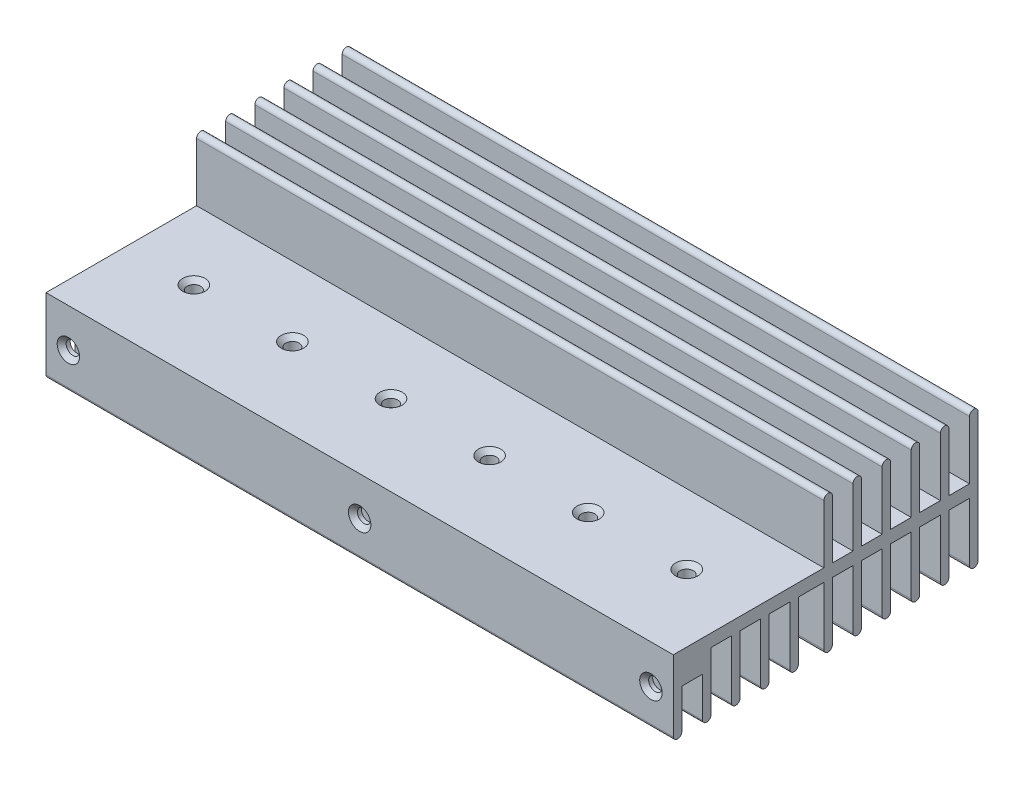
SolidWorks part; units mm, degrees
ref_plane "Front Plane" through (0, 0, 0) normal (0, 0, 1) x (1, 0, 0)
ref_plane "Top Plane" through (0, 0, 0) normal (0, 1, 0) x (1, 0, 0)
ref_plane "Right Plane" through (0, 0, 0) normal (1, 0, 0) x (0, 0, -1)
sketch "Sketch1" plane through (0, 0, 0) normal (1, 0, 0) x (0, 0, -1)
  line L0 (34, 14.4) -> (34, -14.4)
  line L1 (-34, 15.35) -> (34, 15.35) construction
  line L2 (-34, 15.35) -> (-34, -15.35) construction
  line L3 (-34, -15.35) -> (34, -15.35) construction
  line L4 (34, 15.35) -> (34, -15.35) construction
  line L5 (-34, 15.35) -> (34, -15.35) construction
  line L6 (-34, -15.35) -> (34, 15.35) construction
  line L7 (0, 0) -> (47.0202, 0) construction
  line L8 (32.1, 14.4) -> (32.1, 1.4)
  line L9 (25.6, 14.4) -> (25.6, 1.4)
  line L10 (19.1, 14.4) -> (19.1, 1.4)
  line L11 (12.6, 14.4) -> (12.6, 1.4)
  line L12 (6.1, 14.4) -> (6.1, 1.4)
  line L13 (-0.4, 14.4) -> (-0.4, 1.4)
  line L14 (32.1, 1.4) -> (27.5, 1.4)
  line L15 (27.5, 1.4) -> (27.5, 14.4)
  line L16 (25.6, 1.4) -> (21, 1.4)
  line L17 (21, 1.4) -> (21, 14.4)
  line L18 (19.1, 1.4) -> (14.5, 1.4)
  line L19 (14.5, 1.4) -> (14.5, 14.4)
  line L20 (12.6, 1.4) -> (8, 1.4)
  line L21 (8, 1.4) -> (8, 14.4)
  line L22 (6.1, 1.4) -> (1.5, 1.4)
  line L23 (1.5, 1.4) -> (1.5, 14.4)
  line L24 (-0.4, 1.4) -> (-34, 1.4)
  line L25 (-34, 1.4) -> (-34, -14.4922)
  line L26 (-32.1, -14.4922) -> (-32.1, -5.6)
  line L27 (-32.1, -1.4) -> (-27.5, -1.4) construction
  line L28 (-0.4, -14.4) -> (-0.4, -1.4)
  line L29 (1.5, -1.4) -> (1.5, -14.4)
  line L30 (6.1, -1.4) -> (1.5, -1.4)
  line L31 (6.1, -14.4) -> (6.1, -1.4)
  line L32 (8, -1.4) -> (8, -14.4)
  line L33 (12.6, -1.4) -> (8, -1.4)
  line L34 (12.6, -14.4) -> (12.6, -1.4)
  line L35 (14.5, -1.4) -> (14.5, -14.4)
  line L36 (19.1, -1.4) -> (14.5, -1.4)
  line L37 (19.1, -14.4) -> (19.1, -1.4)
  line L38 (21, -1.4) -> (21, -14.4)
  line L39 (25.6, -1.4) -> (21, -1.4)
  line L40 (25.6, -14.4) -> (25.6, -1.4)
  line L41 (27.5, -1.4) -> (27.5, -14.4)
  line L42 (32.1, -1.4) -> (27.5, -1.4)
  line L43 (32.1, -14.4) -> (32.1, -1.4)
  line L44 (-25.6, -14.4922) -> (-25.6, -1.4)
  line L45 (-27.5, -5.6) -> (-27.5, -14.4922)
  line L46 (-19.1, -14.4922) -> (-19.1, -1.4)
  line L47 (-21, -1.4) -> (-21, -14.4922)
  line L48 (-12.6, -14.4922) -> (-12.6, -1.4)
  line L49 (-14.5, -1.4) -> (-14.5, -14.4922)
  line L50 (-6.1, -14.4922) -> (-6.1, -1.4)
  line L51 (-8, -1.4) -> (-8, -14.4922)
  line L52 (-0.4, -1.4) -> (-6.1, -1.4)
  line L53 (-25.6, -1.4) -> (-21, -1.4)
  line L54 (-19.1, -1.4) -> (-14.5, -1.4)
  line L55 (-12.6, -1.4) -> (-8, -1.4)
  line L56 (-32.1, -5.6) -> (-27.5, -5.6)
  line L57 (-32.1, -5.6) -> (-32.1, -1.4) construction
  line L58 (-27.5, -1.4) -> (-27.5, -5.6) construction
  arc A0 (34, 14.4) -> (32.1, 14.4) centre (33.05, 14.4) ccw
  arc A1 (27.5, 14.4) -> (25.6, 14.4) centre (26.55, 14.4) ccw
  arc A2 (21, 14.4) -> (19.1, 14.4) centre (20.05, 14.4) ccw
  arc A3 (14.5, 14.4) -> (12.6, 14.4) centre (13.55, 14.4) ccw
  arc A4 (8, 14.4) -> (6.1, 14.4) centre (7.05, 14.4) ccw
  arc A5 (1.5, 14.4) -> (-0.4, 14.4) centre (0.55, 14.4) ccw
  arc A6 (-34, -14.4922) -> (-32.1, -14.4922) centre (-33.05, -14.395) ccw
  arc A7 (27.5, -14.4) -> (25.6, -14.4) centre (26.55, -14.4) cw
  arc A8 (21, -14.4) -> (19.1, -14.4) centre (20.05, -14.4) cw
  arc A9 (14.5, -14.4) -> (12.6, -14.4) centre (13.55, -14.4) cw
  arc A10 (8, -14.4) -> (6.1, -14.4) centre (7.05, -14.4) cw
  arc A11 (1.5, -14.4) -> (-0.4, -14.4) centre (0.55, -14.4) cw
  arc A12 (34, -14.4) -> (32.1, -14.4) centre (33.05, -14.4) cw
  arc A13 (-27.5, -14.4922) -> (-25.6, -14.4922) centre (-26.55, -14.395) ccw
  arc A14 (-21, -14.4922) -> (-19.1, -14.4922) centre (-20.05, -14.395) ccw
  arc A15 (-14.5, -14.4922) -> (-12.6, -14.4922) centre (-13.55, -14.395) ccw
  arc A16 (-8, -14.4922) -> (-6.1, -14.4922) centre (-7.05, -14.395) ccw
  point P0 (0, 0)
  dimension "D3" = 1.9
  dimension "D8" = 1.9
  dimension "D1" = 30.7
  dimension "D2" = 68
  dimension "D4" = 2.8
  dimension "D6" = 5
  dimension "D7" = 4.6
  dimension "D9" = 2.8
  dimension "D10" = 4.6
  dimension "D11" = 5
  dimension "D12" = 7
  dimension "D5" = 6
extrude "Boss-Extrude1" add sketch "Sketch1" along normal mid plane 140
sketch "Sketch2" plane through (0, 1.4, 0) normal (0, 1, 0) x (1, 0, 0)
  line L0 (70, -34) -> (-70, -34) construction
  line L1 (0, 34) -> (0, -34) construction
  line L2 (70, 34) -> (-70, 34) construction
  line L3 (70, -0.4) -> (70, -34) construction
  circle A0 centre (55, -16) radius 1.5
  circle A1 centre (33, -16) radius 1.5
  circle A2 centre (11, -16) radius 1.5
  circle A3 centre (-55, -16) radius 1.5
  circle A4 centre (-33, -16) radius 1.5
  circle A5 centre (-11, -16) radius 1.5
  dimension "D1" = 18
  dimension "D2" = 3
  dimension "D4" = 22
  dimension "D5" = 15
  dimension "D3" = 3
extrude "Cut-Extrude1" cut sketch "Sketch2" against normal through all both and the other way through all
sketch "Sketch3" plane through (0, 0, 34) normal (0, 0, 1) x (1, 0, 0)
  line L0 (70, 1.4) -> (70, -14.4922) construction
  line L1 (65, -8.75) -> (65, -5.75) construction
  line L2 (70, -15.35) -> (60.7223, -15.35) construction
  line L3 (-70, -15.35) -> (70, -15.35) construction
  line L4 (0, 1.4) -> (0, -15.35) construction
  line L5 (70, 1.4) -> (-70, 1.4) construction
  line L6 (65, -7.25) -> (0, -7.25) construction
  circle A0 centre (65, -7.25) radius 1.5
  circle A1 centre (0, -7.25) radius 1.5
  circle A2 centre (-65, -7.25) radius 1.5
  point P18 (0, 0)
  dimension "D1" = 5
  dimension "D3" = 3
  dimension "D2" = 6.6
extrude "Cut-Extrude2" cut sketch "Sketch3" against normal blind 3 and the other way through all
chamfer "Chamfer1" distance 1 angle 45 9 edges at (55, 1.4, 14.5) (33, 1.4, 14.5) (11, 1.4, 14.5) (-11, 1.4, 14.5) (-33, 1.4, 14.5) (-55, 1.4, 14.5) (-65, -5.75, 34) (0, -5.75, 34) (65, -5.75, 34)
